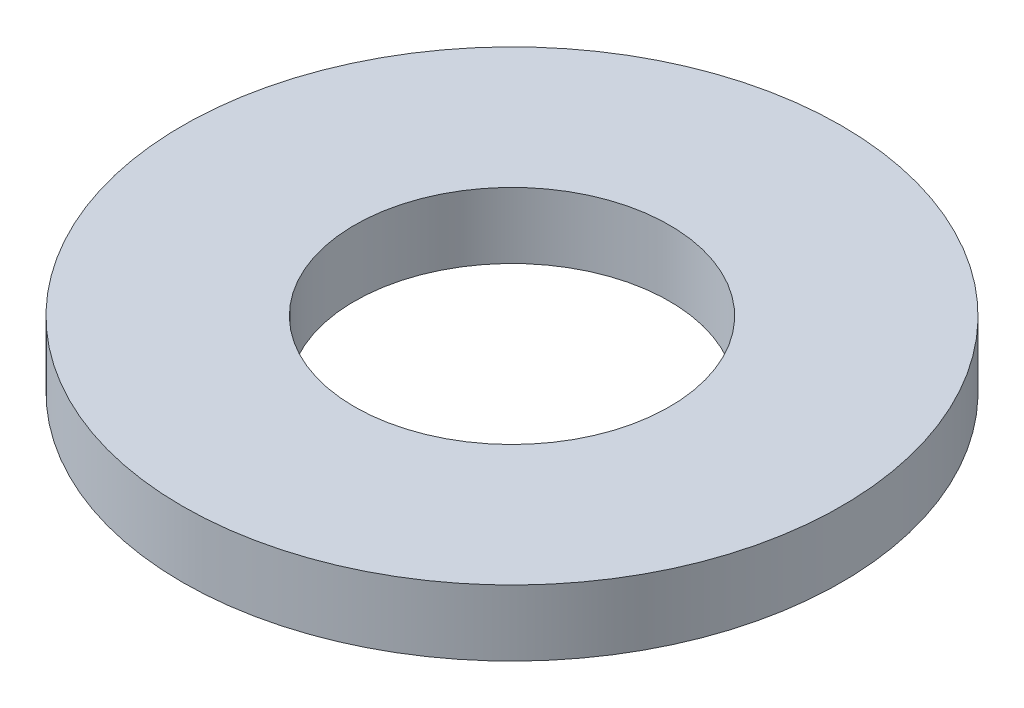
SolidWorks part; units mm, degrees
material "1.0037 (S235JR)"
ref_plane "Front Plane" through (0, 0, 0) normal (0, 0, 1) x (1, 0, 0)
ref_plane "Top Plane" through (0, 0, 0) normal (0, 1, 0) x (1, 0, 0)
ref_plane "Right Plane" through (0, 0, 0) normal (1, 0, 0) x (0, 0, -1)
sketch "Çizim3" plane through (0, 0, 0) normal (0, 1, 0) x (1, 0, 0)
  circle A0 centre (0, 0) radius 1.6
  circle A1 centre (0, 0) radius 3.5
  dimension "D1" = 3.2
  dimension "D2" = 7
extrude "M3" [suppressed] add sketch "Çizim3" along normal blind 0.55
sketch "Çizim2" plane through (0, 0, 0) normal (0, 1, 0) x (1, 0, 0)
  circle A0 centre (0, 0) radius 2.15
  circle A1 centre (0, 0) radius 4.5
  dimension "D1" = 9
  dimension "D2" = 4.3
extrude "M4" add sketch "Çizim2" along normal blind 0.9
sketch "Çizim1" plane through (0, 0, 0) normal (0, 1, 0) x (1, 0, 0)
  circle A0 centre (0, 0) radius 2.65
  circle A1 centre (0, 0) radius 5
  dimension "D1" = 5.3
  dimension "D2" = 10
extrude "M5" [suppressed] add sketch "Çizim1" along normal blind 1
sketch "Çizim4" plane through (0, 0, 0) normal (0, 1, 0) x (1, 0, 0)
  circle A0 centre (0, 0) radius 3.2
  circle A1 centre (0, 0) radius 6
  dimension "D1" = 6.4
  dimension "D2" = 12
extrude "M6" [suppressed] add sketch "Çizim4" along normal blind 1.8
sketch "Çizim5" plane through (0, 0, 0) normal (0, 1, 0) x (1, 0, 0)
  circle A0 centre (0, 0) radius 3.7
  circle A1 centre (0, 0) radius 7
  dimension "D1" = 14
  dimension "D2" = 7.4
extrude "M7" [suppressed] add sketch "Çizim5" along normal blind 1.8
sketch "Çizim6" plane through (0, 0, 0) normal (0, 1, 0) x (1, 0, 0)
  circle A0 centre (0, 0) radius 4.2
  circle A1 centre (0, 0) radius 8
  dimension "D1" = 8.4
  dimension "D2" = 16
extrude "M8" [suppressed] add sketch "Çizim6" along normal blind 1.8
sketch "Çizim7" plane through (0, 0, 0) normal (0, 1, 0) x (1, 0, 0)
  circle A0 centre (0, 0) radius 5.25
  circle A1 centre (0, 0) radius 10
  dimension "D1" = 10.5
  dimension "D2" = 20
extrude "M10" [suppressed] add sketch "Çizim7" along normal blind 2.2
sketch "Çizim8" plane through (0, 0, 0) normal (0, 1, 0) x (1, 0, 0)
  circle A0 centre (0, 0) radius 12
  circle A1 centre (-0.3048, 0.3048) radius 6.5
  dimension "D1" = 13
  dimension "D2" = 24
extrude "M12" [suppressed] add sketch "Çizim8" along normal blind 2.7
sketch "Çizim9" plane through (0, 0, 0) normal (0, 1, 0) x (1, 0, 0)
  circle A0 centre (0, 0) radius 7.5
  circle A1 centre (0, 0) radius 14
  dimension "D1" = 15
  dimension "D2" = 28
extrude "M14" [suppressed] add sketch "Çizim9" along normal blind 2.7
sketch "Çizim10" plane through (0, 0, 0) normal (0, 1, 0) x (1, 0, 0)
  circle A0 centre (0, 0) radius 8.5
  circle A1 centre (0, 0) radius 15
  dimension "D1" = 17
  dimension "D2" = 30
extrude "M16 " [suppressed] add sketch "Çizim10" along normal blind 3.3
